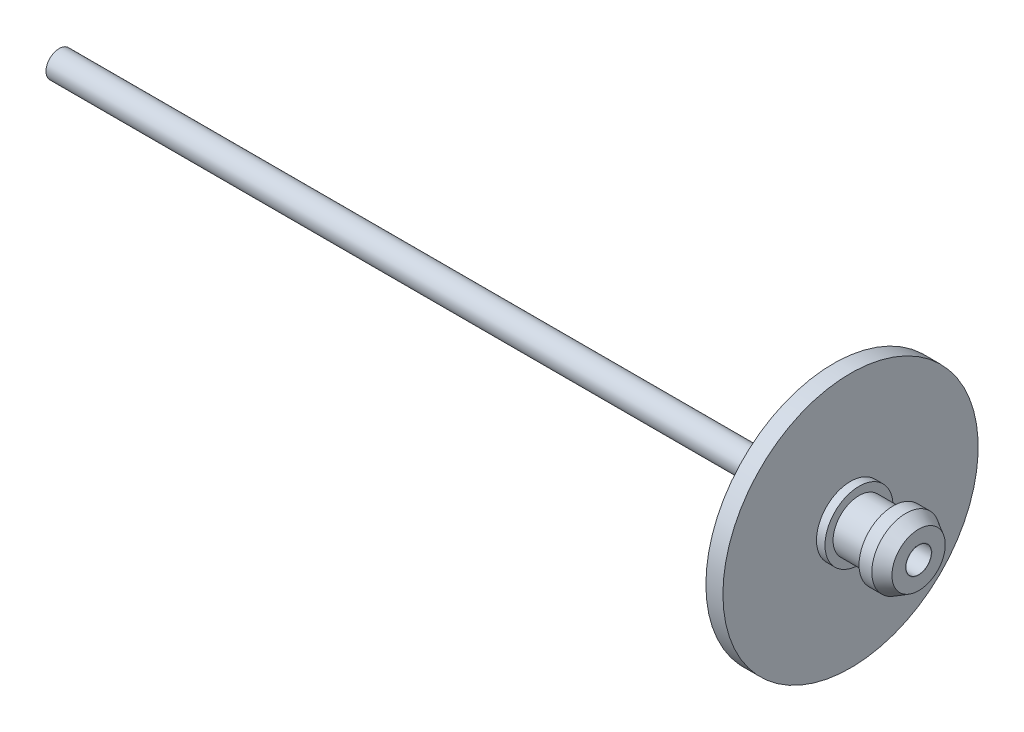
SolidWorks part; units mm, degrees
ref_plane "Спереди" through (0, 0, 0) normal (0, 0, 1) x (1, 0, 0)
ref_plane "Сверху" through (0, 0, 0) normal (0, 1, 0) x (1, 0, 0)
ref_plane "Справа" through (0, 0, 0) normal (1, 0, 0) x (0, 0, -1)
sketch "Эскиз1" plane through (0, 0, 0) normal (0, 0, 1) x (1, 0, 0)
  line L0 (0, 21.9585) -> (0, 30)
  line L1 (0, 30) -> (4, 30)
  line L2 (4, 30) -> (4, 8)
  line L3 (4, 8) -> (5.9958, 8)
  line L4 (5.9958, 8) -> (5.9958, 6.1)
  line L5 (5.9958, 6.1) -> (13.9958, 6.1)
  line L9 (20, 6.2679) -> (20, 3.1)
  line L10 (20, 3.1) -> (0, 3.1)
  line L11 (0, 3.1) -> (0, 21.9585)
  line L12 (0, 0) -> (164.4372, 0) construction
  line L13 (13.9958, 6.1) -> (13.9958, 8)
  line L14 (13.9958, 8) -> (17, 8)
  line L15 (17, 8) -> (20, 6.2679)
  dimension "D1" = 6.2
  dimension "D2" = 60
  dimension "D3" = 16
  dimension "D4" = 120
  dimension "D5" = 4
  dimension "D6" = 3
  dimension "D7" = 8
  dimension "D8" = 20
  dimension "D9" = 3
revolve "Повернуть1" add sketch "Эскиз1" angle 360 about L12
sketch "Эскиз3" plane through (20, 0, 0) normal (1, 0, 0) x (0, 0, -1)
  circle A0 centre (0, 0) radius 3.1 construction
  circle A1 centre (0, 0) radius 3.1
  circle A2 centre (0, 0) radius 3
  dimension "D1" = 0.1
extrude "Бобышка-Вытянуть1" add sketch "Эскиз3" against normal blind 202 separate body
